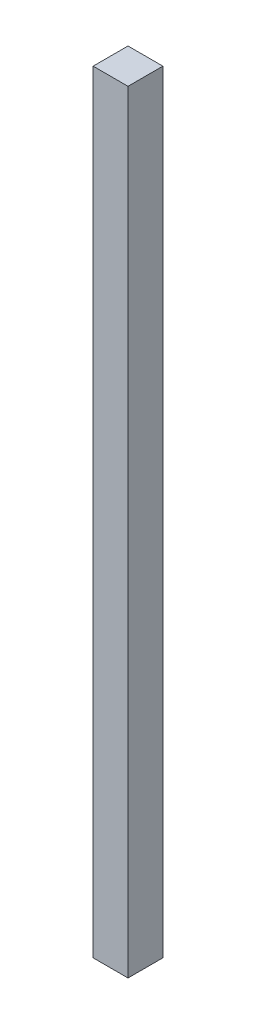
SolidWorks part; units mm, degrees
ref_plane "Front Plane" through (0, 0, 0) normal (0, 0, 1) x (1, 0, 0)
ref_plane "Top Plane" through (0, 0, 0) normal (0, 1, 0) x (1, 0, 0)
ref_plane "Right Plane" through (0, 0, 0) normal (1, 0, 0) x (0, 0, -1)
sketch "Sketch1" plane through (0, 0, 0) normal (0, 1, 0) x (1, 0, 0)
  line L1 (-7.9057, 7.9057) -> (7.9057, 7.9057)
  line L2 (-7.9057, 7.9057) -> (-7.9057, -7.9057)
  line L3 (-7.9057, -7.9057) -> (7.9057, -7.9057)
  line L4 (7.9057, 7.9057) -> (7.9057, -7.9057)
  line L5 (-7.9057, 7.9057) -> (7.9057, -7.9057) construction
  line L6 (-7.9057, -7.9057) -> (7.9057, 7.9057) construction
  point P0 (0, 0)
  dimension "D1" = 15.8114
  dimension "D2" = 15.8114
extrude "Boss-Extrude1" add sketch "Sketch1" along normal blind 350
